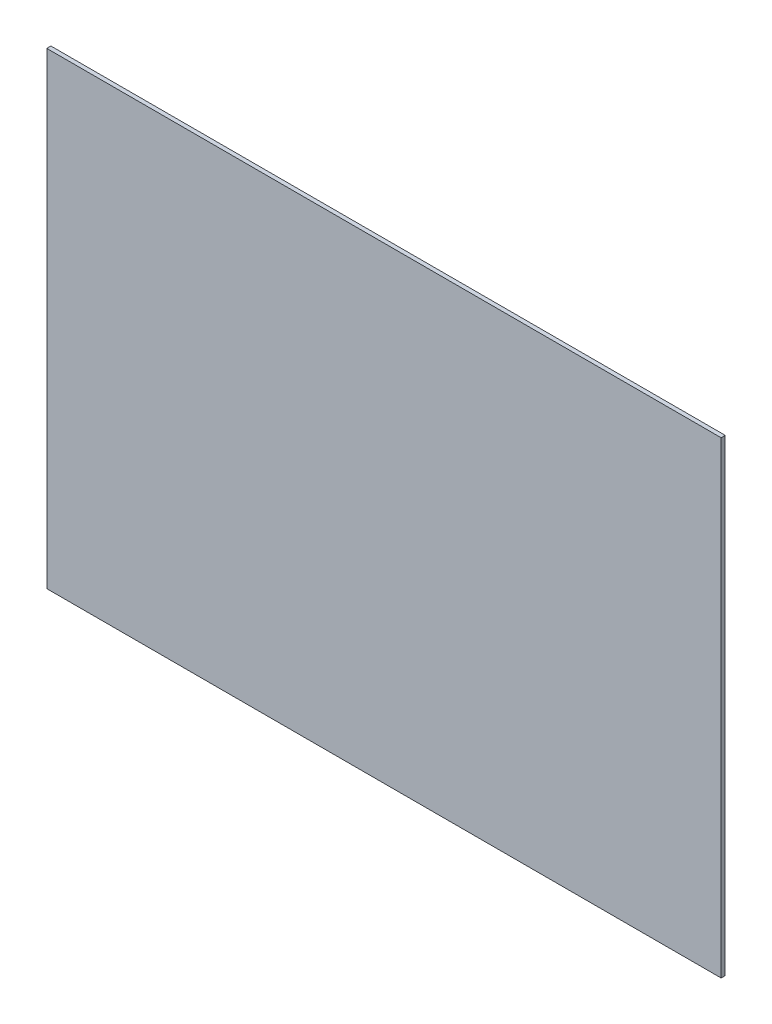
SolidWorks part; units mm, degrees
ref_plane "Face" through (0, 0, 0) normal (0, 0, 1) x (1, 0, 0)
ref_plane "Dessus" through (0, 0, 0) normal (0, 1, 0) x (1, 0, 0)
ref_plane "Droite" through (0, 0, 0) normal (1, 0, 0) x (0, 0, -1)
sketch "Esquisse1" plane through (0, 0, 0) normal (0, 0, 1) x (1, 0, 0)
  line L1 (-32.0766, 7.7836) -> (16.9234, 7.7836)
  line L2 (-32.0766, 7.7836) -> (-32.0766, -26.2164)
  line L3 (-32.0766, -26.2164) -> (16.9234, -26.2164)
  line L4 (16.9234, 7.7836) -> (16.9234, -26.2164)
  dimension "D1" = 34
  dimension "D2" = 49
extrude "Extrusion1" add sketch "Esquisse1" against normal blind 0.3
sketch "Esquisse3" plane through (-46.087, -30.917, 0) normal (0, 0, 1) x (1, 0, 0)
  line L0 (24.3867, 34.7864) -> (29.1529, 26.8427)
  line L1 (19.6205, 26.8427) -> (29.1529, 26.8427)
  line L2 (24.3867, 35.3695) -> (29.6827, 26.5427)
  line L3 (19.0906, 26.5427) -> (29.6827, 26.5427)
  line L4 (19.6205, 26.8427) -> (24.3867, 34.7864)
  line L5 (19.0906, 26.5427) -> (24.3867, 35.3695)
  line L14 (41.6344, 10.0239) -> (47.0104, 10.0239)
  line L15 (41.6344, 14.5039) -> (47.0104, 14.5039)
  line L16 (47.0104, 14.5039) -> (47.0104, 10.0239)
  line L17 (41.6344, 14.5039) -> (41.6344, 10.0239)
  line L18 (41.9032, 14.2351) -> (46.7416, 14.2351)
  line L19 (46.7416, 14.2351) -> (46.7416, 10.2927)
  line L20 (41.9032, 10.2927) -> (46.7416, 10.2927)
  line L21 (41.9032, 14.2351) -> (41.9032, 10.2927)
extrude "Enlèv. mat.-Extru.1" [suppressed] cut sketch "Esquisse3" against normal blind 0.1
sketch "Esquisse4" [suppressed] plane through (-52.7798, -14.9304, 0) normal (0, 0, 1) x (1, 0, 0)
  line L0 (31.0795, 18.7998) -> (31.0795, 10.8561) construction
  line L1 (26.3133, 10.8561) -> (35.8457, 10.8561) construction
  line L2 (30.931, 17.7188) -> (31.231, 17.7188)
  line L3 (30.931, 17.7188) -> (30.931, 12.6358)
  line L4 (30.931, 12.6358) -> (31.231, 12.6358)
  line L5 (31.231, 17.7188) -> (31.231, 12.6358)
  circle A0 centre (31.0795, 11.8893) radius 0.2849
  dimension "D1" = 0.3
extrude "Enlèv. mat.-Extru.3" [suppressed] cut sketch "Esquisse4" against normal blind 0.1
sketch "Esquisse2" plane through (-64.6539, -34.7051, 0) normal (0, 0, 1) x (1, 0, 0)
  line L15 (62.4103, 15.6784) -> (61.7635, 14.473)
  line L16 (62.9189, 15.8647) -> (62.172, 14.473)
  line L17 (62.9189, 15.8647) -> (63.6658, 14.473)
  line L18 (62.172, 14.473) -> (61.7635, 14.473)
  line L19 (62.4103, 16.9534) -> (63.4275, 16.9534)
  line L20 (62.4103, 16.9534) -> (61.6447, 16.3697)
  line L21 (63.4275, 15.6784) -> (64.0743, 14.473)
  line L22 (63.6658, 14.473) -> (64.0743, 14.473)
  line L23 (63.4275, 15.6784) -> (63.4275, 16.6139)
  line L24 (62.4103, 15.6784) -> (62.4103, 16.6139)
  line L25 (62.4103, 16.6139) -> (61.8084, 16.155)
  line L26 (63.4275, 16.6139) -> (64.0294, 16.155)
  line L27 (63.4275, 16.9534) -> (64.1931, 16.3697)
  line L28 (61.8084, 16.155) -> (61.6447, 16.3697)
  line L29 (64.0294, 16.155) -> (64.1931, 16.3697)
  circle A1 centre (62.9189, 17.4102) radius 0.36
extrude "Enlèv. mat.-Extru.2" [suppressed] cut sketch "Esquisse2" against normal blind 0.1
sketch "Esquisse5" plane through (-65.3769, -34.6785, 0) normal (0, 0, 1) x (1, 0, 0)
  line L8 (70.0227, 16.8131) -> (70.0227, 15.2771)
  line L9 (69.7827, 17.0051) -> (72.6723, 17.0051)
  line L10 (69.7827, 17.0051) -> (69.7827, 15.0851)
  line L11 (69.7827, 15.0851) -> (72.6723, 15.0851)
  line L12 (72.6723, 17.0051) -> (72.6723, 15.0851)
  line L13 (70.0227, 15.2771) -> (72.4323, 15.2771)
  line L14 (72.4323, 16.8131) -> (72.4323, 15.2771)
  line L15 (70.0227, 16.8131) -> (72.4323, 16.8131)
extrude "Enlèv. mat.-Extru.4" [suppressed] cut sketch "Esquisse5" against normal blind 0.1
sketch "Esquisse6" plane through (0, 0, 0) normal (0, 0, 1) x (1, 0, 0)
  line L10 (3.3658, -16.4135) -> (3.3658, -20.8935)
  line L11 (3.3658, -20.8935) -> (8.3354, -20.8935)
  line L12 (8.3354, -20.8935) -> (8.3354, -16.4135)
  line L13 (8.3354, -16.4135) -> (3.3658, -16.4135)
  line L18 (3.6058, -20.6535) -> (8.0954, -20.6535)
  line L19 (8.0954, -20.6535) -> (8.0954, -16.6535)
  line L20 (8.0954, -16.6535) -> (3.6058, -16.6535)
  line L21 (3.6058, -16.6535) -> (3.6058, -20.6535)
extrude "Enlèv. mat.-Extru.5" [suppressed] cut sketch "Esquisse6" against normal blind 0.1
sketch "Esquisse7" plane through (0, 0, 0) normal (0, 0, 1) x (1, 0, 0)
  text T0 "IP 31" font "Century Gothic" height 2
extrude "Enlèv. mat.-Extru.6" [suppressed] cut sketch "Esquisse7" against normal blind 0.1
sketch "Esquisse10" plane through (0, 0, 0) normal (0, 0, 1) x (1, 0, 0)
  line L1 (-6.4726, 5.7346) -> (11.6053, 5.7346)
  line L2 (-7.4726, 4.7346) -> (-7.4726, -5.8691)
  line L3 (-6.4726, -6.8691) -> (11.6053, -6.8691)
  line L4 (12.6053, 4.7346) -> (12.6053, -5.8691)
  arc A0 (-7.4726, 4.7346) -> (-6.4726, 5.7346) centre (-6.4726, 4.7346) cw
  arc A1 (12.6053, 4.7346) -> (11.6053, 5.7346) centre (11.6053, 4.7346) ccw
  arc A2 (11.6053, -6.8691) -> (12.6053, -5.8691) centre (11.6053, -5.8691) ccw
  arc A3 (-7.4726, -5.8691) -> (-6.4726, -6.8691) centre (-6.4726, -5.8691) ccw
extrude "Enlèv. mat.-Extru.9" [suppressed] cut sketch "Esquisse10" against normal blind 0.1
sketch "Esquisse11" [suppressed] plane through (0, 0, -0.1) normal (0, 0, 1) x (1, 0, 0)
  line L0 (-10.5001, -7.3009) -> (-10.5237, -7.8004)
  line L1 (-3.267, -2.0025) -> (-2.9182, -2.616)
  line L2 (-2.9182, -2.616) -> (-2.0613, -0.5916)
  line L3 (-12.1634, -9.0683) -> (2.5663, 3.2914) construction
  line L4 (2.5663, 3.2914) -> (-2.7157, -8.0359) construction
  line L5 (-4.2037, -1.0839) -> (-2.0613, -0.5916)
  line L6 (-3.6021, -1.6037) -> (-4.2037, -1.0839)
  line L8 (2.5663, 5.7346) -> (2.5663, -10.4842) construction
  line L9 (11.6053, 5.7346) -> (-6.4726, 5.7346) construction
  line L10 (2.2098, -4.5893) -> (1.5663, -4.7072)
  line L11 (2.7382, -4.5734) -> (3.5663, -4.7072)
  line L12 (3.5663, -4.7072) -> (2.5663, -2.7495)
  line L13 (1.5663, -4.7072) -> (2.5663, -2.7495)
  line L14 (15.6328, -7.3009) -> (15.6563, -7.8004)
  line L15 (8.7347, -1.6037) -> (9.3364, -1.0839)
  line L16 (8.3996, -2.0025) -> (8.0508, -2.616)
  line L17 (8.0508, -2.616) -> (7.1939, -0.5916)
  line L18 (9.3364, -1.0839) -> (7.1939, -0.5916)
  line L20 (2.2308, -15.934) -> (2.5663, 3.2914) construction
  line L21 (3.0632, -11.3362) -> (3.5684, -11.3362)
  line L22 (1.9881, -13.5191) -> (2.3496, -13.8646) [skipped]
  arc A0 (-3.6021, -1.6037) -> (-6.6513, -4.9941) centre (-1.2329, -6.8008) ccw
  arc A1 (-6.6513, -4.9941) -> (-10.5001, -7.3009) centre (-10.3093, -3.255) cw
  arc A2 (-3.267, -2.0025) -> (-6.186, -5.1797) centre (-1.2329, -6.8008) ccw
  arc A3 (-6.186, -5.1797) -> (-10.5237, -7.8004) centre (-10.3093, -3.255) cw
  arc A4 (-3.3947, -2.0586) -> (-6.186, -5.1797) centre (-1.2329, -6.8008) ccw construction
  arc A5 (2.2098, -4.5893) -> (2.7722, -9.1009) centre (7.6905, -6.197) ccw
  arc A6 (2.7722, -9.1009) -> (3.0632, -11.3362) centre (-0.9402, -10.7208) cw
  arc A7 (2.7382, -4.5734) -> (3.2175, -8.8716) centre (7.6905, -6.197) ccw
  arc A8 (3.2175, -8.8716) -> (3.5684, -11.3362) centre (-0.9402, -10.7208) cw
  arc A9 (11.7839, -4.9941) -> (15.6328, -7.3009) centre (15.442, -3.255) ccw
  arc A10 (11.3187, -5.1797) -> (15.6563, -7.8004) centre (15.442, -3.255) ccw
  arc A11 (8.7347, -1.6037) -> (11.7839, -4.9941) centre (6.3655, -6.8008) cw
  arc A12 (8.3996, -2.0025) -> (11.3187, -5.1797) centre (6.3655, -6.8008) cw
  dimension "D1" = 0.5
  dimension "D2" = 2
  dimension "D3" = 25
  dimension "D4" = 50
extrude "Extrusion2" [suppressed] add sketch "Esquisse11" along normal blind 0.2
sketch "Esquisse12" plane through (0, 0, 0) normal (0, 0, 1) x (1, 0, 0)
  line L0 (-28.5046, -21.5279) -> (-28.5046, -20.8279)
  line L1 (-28.5046, -16.6279) -> (-28.5046, -15.9279)
  line L2 (-24.6669, -15.9279) -> (-24.6669, -16.6279)
  line L3 (-24.6669, -20.8279) -> (-24.6669, -21.5279)
  line L4 (-26.7375, -18.3779) -> (-25.1199, -18.3779)
  line L5 (-26.7375, -19.0779) -> (-25.1199, -19.0779)
  line L6 (-25.1199, -18.3779) -> (-25.1199, -19.0779)
  arc A0 (-28.5046, -16.6279) -> (-28.5046, -20.8279) centre (-28.5046, -18.7279) ccw
  arc A1 (-28.5046, -15.9279) -> (-28.5046, -21.5279) centre (-28.5046, -18.7279) ccw
  arc A2 (-26.7375, -19.0779) -> (-24.6669, -20.8279) centre (-24.6669, -18.7279) ccw
  arc A3 (-24.6669, -16.6279) -> (-26.7375, -18.3779) centre (-24.6669, -18.7279) ccw
  arc A4 (-24.6669, -15.9279) -> (-24.6669, -21.5279) centre (-24.6669, -18.7279) ccw
extrude "Extrusion3" [suppressed] add sketch "Esquisse12" along normal blind 0.1
sketch "Esquisse13" plane through (0, 0, 0) normal (0, 0, 1) x (1, 0, 0)
  text T0 "0123" font "Century Gothic" height 2
extrude "Extrusion4" [suppressed] add sketch "Esquisse13" along normal blind 0.1
sketch "Esquisse14" plane through (0, 0, 0) normal (0, 0, 1) x (1, 0, 0)
  line L0 (16.9234, -12.2164) -> (-32.0766, -12.2164)
  line L3 (-32.0766, -12.1164) -> (-32.0766, -12.2164)
  line L4 (16.9234, -12.2164) -> (16.9234, -12.1164)
  line L5 (16.9234, -12.1164) -> (-32.0766, -12.1164)
extrude "Enlèv. mat.-Extru.10" [suppressed] cut sketch "Esquisse14" against normal blind 0.1
sketch "Esquisse16" plane through (0, 0, 0) normal (0, 0, 1) x (1, 0, 0)
  line L0 (-10.9492, -13.2587) -> (-10.9492, -23.1635) construction
  line L1 (-12.3256, -15.977) -> (-12.161, -15.9768)
  line L2 (-12.161, -15.4971) -> (-11.8613, -15.4971)
  line L3 (-14.5492, -14.9342) -> (-12.4221, -17.1511)
  line L4 (-7.3492, -14.7031) -> (-9.0529, -16.4788)
  line L5 (-14.5492, -14.7031) -> (-12.446, -16.8951)
  line L6 (-7.3492, -14.9342) -> (-8.8312, -16.4788)
  line L7 (-12.161, -15.4971) -> (-12.161, -15.6344)
  line L8 (-11.1702, -15.6081) -> (-10.4885, -15.6081)
  line L9 (-14.5492, -22.2072) -> (-14.4337, -22.318)
  line L10 (-7.3492, -22.2072) -> (-7.4646, -22.318)
  line L11 (-10.8383, -18.5707) -> (-9.5746, -19.8878)
  line L12 (-11.06, -18.5707) -> (-12.0342, -19.586)
  line L13 (-14.5492, -14.7031) -> (-14.5492, -14.9342)
  line L14 (-10.9492, -18.6863) -> (-9.5889, -20.104)
  line L15 (-7.3492, -14.9342) -> (-7.3492, -14.7031)
  line L16 (-10.9492, -18.6863) -> (-12.0145, -19.7966)
  line L17 (-14.1989, -18.5707) -> (-5.746, -18.5707) construction
  line L18 (-12.84, -16.1307) -> (-12.84, -15.9777)
  line L19 (-12.3566, -16.1307) -> (-9.3255, -16.1307)
  line L20 (-9.4065, -17.0784) -> (-10.8383, -18.5707)
  line L21 (-12.84, -16.1307) -> (-12.5173, -16.1307)
  line L22 (-8.9912, -16.6456) -> (-9.2465, -16.9117)
  line L23 (-9.3255, -16.1307) -> (-9.3485, -16.4788)
  line L24 (-11.9013, -21.0107) -> (-10.307, -21.0107)
  line L25 (-11.9013, -21.0107) -> (-12.0145, -19.7966)
  line L26 (-12.84, -15.9777) -> (-12.5133, -15.9773)
  line L27 (-9.1669, -16.1579) -> (-9.1882, -16.4788)
  line L28 (-12.047, -21.1707) -> (-11.9857, -21.1707)
  line L29 (-12.047, -21.1707) -> (-12.161, -19.9493)
  line L30 (-9.3931, -17.1511) -> (-9.5746, -19.8878)
  line L31 (-9.2328, -17.1511) -> (-9.4246, -20.0441)
  line L32 (-12.446, -16.8951) -> (-12.5173, -16.1307)
  line L33 (-12.268, -17.0807) -> (-10.9492, -18.4552)
  line L34 (-12.268, -17.0807) -> (-12.3566, -16.1307)
  line L35 (-12.2441, -17.3366) -> (-11.06, -18.5707)
  line L36 (-12.1807, -19.7387) -> (-14.5492, -22.2072)
  line L37 (-12.1807, -19.7387) -> (-12.4221, -17.1511)
  line L38 (-12.0342, -19.586) -> (-12.2441, -17.3366)
  line L39 (-12.161, -19.9493) -> (-14.4337, -22.318)
  line L40 (-9.5889, -20.104) -> (-9.5952, -20.1988)
  line L41 (-9.4246, -20.0441) -> (-7.3492, -22.2072)
  line L42 (-10.1186, -17.5895) -> (-11.3302, -17.5895)
  line L43 (-8.973, -20.7459) -> (-7.4646, -22.318)
  line L44 (-11.8613, -15.9765) -> (-9.4065, -15.9735)
  line L45 (-11.3302, -15.3632) -> (-10.3285, -15.3632)
  line L46 (-11.3302, -15.3632) -> (-11.3302, -15.4442)
  line L47 (-11.3302, -15.7681) -> (-10.3285, -15.7681)
  line L48 (-10.3285, -15.3632) -> (-10.3285, -15.4542)
  line L49 (-10.4885, -15.5232) -> (-10.4885, -15.6081)
  line L50 (-11.1702, -15.5232) -> (-10.4885, -15.5232)
  line L51 (-11.1702, -15.5232) -> (-11.1702, -15.6081)
  line L52 (-11.3302, -15.6048) -> (-11.3302, -15.7681)
  line L53 (-10.3285, -15.6152) -> (-10.3285, -15.7681)
  line L54 (-12.161, -15.8193) -> (-12.161, -15.9768)
  line L55 (-9.1882, -16.4788) -> (-9.0529, -16.4788)
  line L56 (-9.4065, -17.1511) -> (-9.3931, -17.1511)
  line L57 (-9.4065, -17.1511) -> (-9.4065, -17.0784)
  line L58 (-9.4065, -16.4788) -> (-9.3485, -16.4788)
  line L59 (-8.8312, -17.1511) -> (-8.8312, -16.4788)
  line L60 (-9.2328, -17.1511) -> (-8.8312, -17.1511)
  line L61 (-9.4065, -16.8473) -> (-9.4065, -16.4788)
  line L62 (-9.2465, -16.9911) -> (-8.9912, -16.9911)
  line L63 (-8.9912, -16.9911) -> (-8.9912, -16.6456)
  line L64 (-11.5459, -21.1707) -> (-10.2536, -21.1707)
  line L65 (-9.2465, -16.9911) -> (-9.2465, -16.9117)
  line L66 (-10.1186, -17.5895) -> (-10.9492, -18.4552)
  line L67 (-9.4065, -16.8473) -> (-9.9853, -17.4506)
  line L68 (-11.9857, -21.1707) -> (-11.9857, -21.5053)
  line L69 (-11.9857, -21.5053) -> (-11.5459, -21.5053)
  line L70 (-11.8613, -15.4971) -> (-11.8613, -15.5259)
  line L71 (-11.5459, -21.1707) -> (-11.5459, -21.5053)
  line L72 (-9.9853, -17.4506) -> (-9.9853, -17.2631)
  line L73 (-9.9853, -17.2631) -> (-11.3302, -17.2631)
  line L74 (-11.3302, -17.5895) -> (-11.3302, -17.2631)
  line L75 (-11.8613, -15.6916) -> (-11.8613, -15.9765)
  arc A0 (-9.5952, -20.1988) -> (-10.307, -21.0107) centre (-9.6402, -20.8773) ccw
  arc A1 (-10.2536, -21.1707) -> (-8.973, -20.7459) centre (-9.6402, -20.8773) ccw
  arc A2 (-9.1669, -16.1579) -> (-9.3471, -15.8111) centre (-9.0942, -15.8999) ccw
  circle A3 centre (-9.6402, -20.8773) radius 0.381
  spline S0 degree 3 poles (-11.8613, -15.6916) (-11.8227, -15.6809) (-11.6504, -15.6396) (-11.468, -15.6168) (-11.3302, -15.6048) knots 0.216271 0.216271 0.216271 0.216271 0.25 0.363545 0.363545 0.363545 0.363545
  spline S1 degree 3 poles (-11.8613, -15.5259) (-11.8326, -15.5188) (-11.654, -15.4782) (-11.4766, -15.4566) (-11.3302, -15.4442) knots 0.227473 0.227473 0.227473 0.227473 0.25 0.367501 0.367501 0.367501 0.367501
  spline S2 degree 3 poles (-12.3256, -15.977) (-12.3174, -15.9651) (-12.2715, -15.9029) (-12.2136, -15.8535) (-12.161, -15.8193) knots 0.049255 0.049255 0.049255 0.049255 0.0625 0.120323 0.120323 0.120323 0.120323
  spline S3 degree 3 poles (-10.3285, -15.4542) (-10.1894, -15.4686) (-9.889, -15.5118) (-9.5509, -15.6419) (-9.3853, -15.7773) (-9.3471, -15.8111) knots 0.638997 0.638997 0.638997 0.638997 0.75 0.875 0.914866 0.914866 0.914866 0.914866
  spline S4 degree 3 poles (-12.5133, -15.9773) (-12.5078, -15.9666) (-12.4828, -15.9199) (-12.3995, -15.8001) (-12.2814, -15.7015) (-12.1858, -15.6472) (-12.161, -15.6344) knots 0.021983 0.021983 0.021983 0.021983 0.03125 0.0625 0.125 0.146284 0.146284 0.146284 0.146284
  spline S5 degree 3 poles (-10.3285, -15.6152) (-10.1996, -15.6293) (-9.918, -15.6718) (-9.6122, -15.7904) (-9.4561, -15.9269) (-9.4065, -15.9735) knots 0.643707 0.643707 0.643707 0.643707 0.75 0.875 0.93275 0.93275 0.93275 0.93275
extrude "Enlèv. mat.-Extru.11" [suppressed] cut sketch "Esquisse16" against normal blind 0.1
sketch "Esquisse17" plane through (0, 0, 0) normal (0, 0, 1) x (1, 0, 0)
  line L0 (-13.7173, -24.671) -> (-7.9573, -24.671)
  line L1 (-13.7173, -23.871) -> (-7.9573, -23.871)
  line L2 (-13.7173, -23.871) -> (-13.7173, -24.671)
  line L3 (-7.9573, -23.871) -> (-7.9573, -24.671)
extrude "Enlèv. mat.-Extru.12" [suppressed] cut sketch "Esquisse17" against normal blind 0.1
sketch "Esquisse18" plane through (0, 0, 0) normal (0, 0, 1) x (1, 0, 0)
  text T0 "CSA" font "Century Gothic" height in points 8
extrude "Extrusion5" [suppressed] add sketch "Esquisse18" along normal blind 0.2
